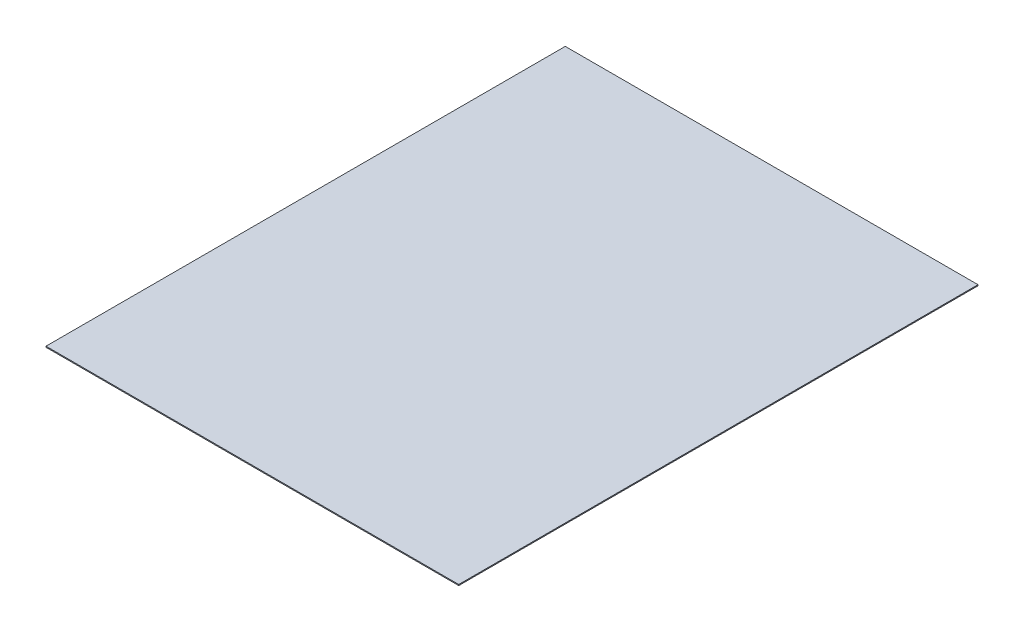
SolidWorks part; units mm, degrees
ref_plane "Front Plane" through (0, 0, 0) normal (0, 0, 1) x (1, 0, 0)
ref_plane "Top Plane" through (0, 0, 0) normal (0, 1, 0) x (1, 0, 0)
ref_plane "Right Plane" through (0, 0, 0) normal (1, 0, 0) x (0, 0, -1)
other "Configuration Table"
sketch "Sketch1" plane through (0, 0, 0) normal (0, 0, 1) x (1, 0, 0)
  line L1 (40, 1072) -> (660, 1072)
  line L2 (40, 1072) -> (40, 1073.5)
  line L3 (40, 1073.5) -> (660, 1073.5)
  line L4 (660, 1072) -> (660, 1073.5)
extrude "PRESS_tepsi_rafi_raf_1" add sketch "Sketch1" against normal blind 780 from offset 20 separate body
